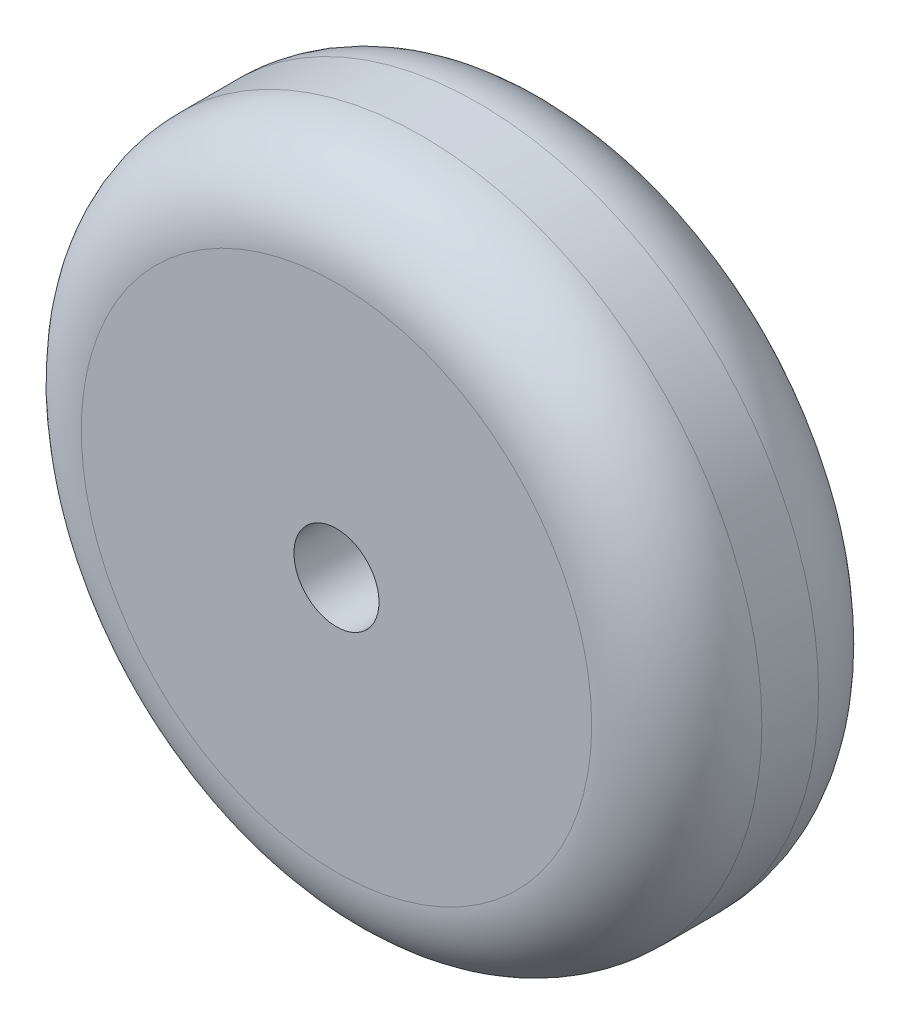
SolidWorks part; units mm, degrees
ref_plane "Front Plane" through (0, 0, 0) normal (0, 0, 1) x (1, 0, 0)
ref_plane "Top Plane" through (0, 0, 0) normal (0, 1, 0) x (1, 0, 0)
ref_plane "Right Plane" through (0, 0, 0) normal (1, 0, 0) x (0, 0, -1)
sketch "Sketch1" plane through (0, 0, 0) normal (0, 0, 1) x (1, 0, 0)
  circle A0 centre (0, 0) radius 6
  dimension "D1" = 12
extrude "Boss-Extrude1" add sketch "Sketch1" along normal mid plane 4
sketch "Sketch2" plane through (0, 0, 0) normal (0, 0, 1) x (1, 0, 0)
  circle A0 centre (0, 0) radius 0.75
extrude "Cut-Extrude1" cut sketch "Sketch2" against normal mid plane 4
fillet "Fillet1" radius 1.5 2 edges at (6, 0, -2) (6, 0, 2)
